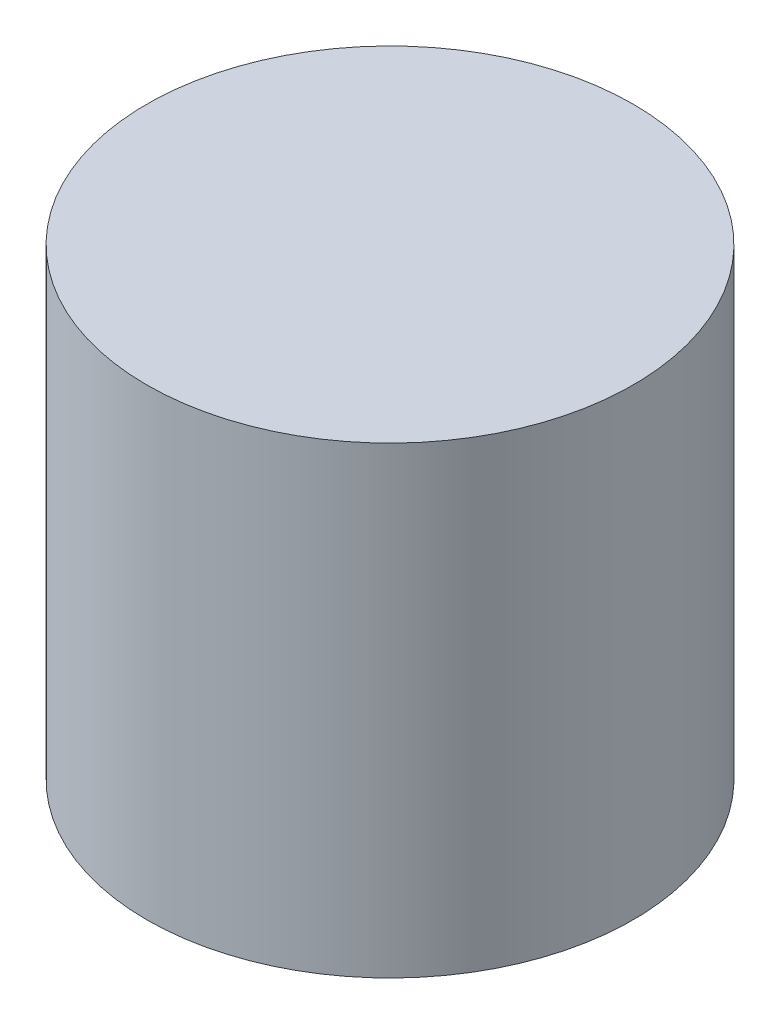
SolidWorks part; units mm, degrees
ref_plane "Alzado" through (0, 0, 0) normal (0, 0, 1) x (1, 0, 0)
ref_plane "Planta" through (0, 0, 0) normal (0, 1, 0) x (1, 0, 0)
ref_plane "Vista lateral" through (0, 0, 0) normal (1, 0, 0) x (0, 0, -1)
sketch "Croquis1" plane through (0, 0, 0) normal (0, 1, 0) x (1, 0, 0)
  circle A0 centre (0, 0) radius 10.5
  dimension "D1" = 21
extrude "Saliente-Extruir1" add sketch "Croquis1" along normal blind 20
